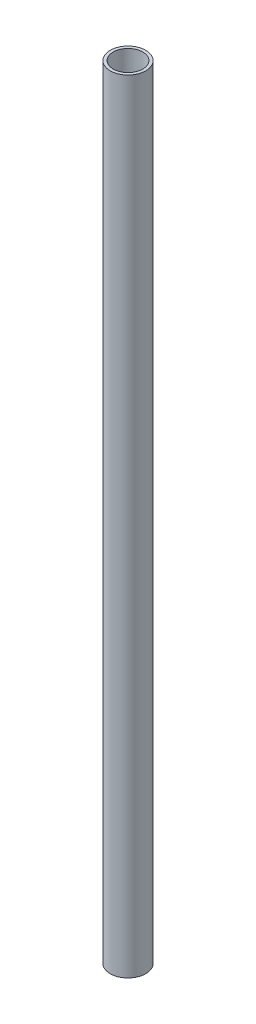
SolidWorks part; units mm, degrees
ref_plane "Front Plane" through (0, 0, 0) normal (0, 0, 1) x (1, 0, 0)
ref_plane "Top Plane" through (0, 0, 0) normal (0, 1, 0) x (1, 0, 0)
ref_plane "Right Plane" through (0, 0, 0) normal (1, 0, 0) x (0, 0, -1)
sketch "Sketch1" plane through (0, 0, 0) normal (0, 1, 0) x (1, 0, 0)
  circle A0 centre (0, 0) radius 21.082
  circle A1 centre (0, 0) radius 17.526
  dimension "D1" = 42.164
  dimension "D2" = 35.052
extrude "Boss-Extrude1" add sketch "Sketch1" along normal blind 927.1
